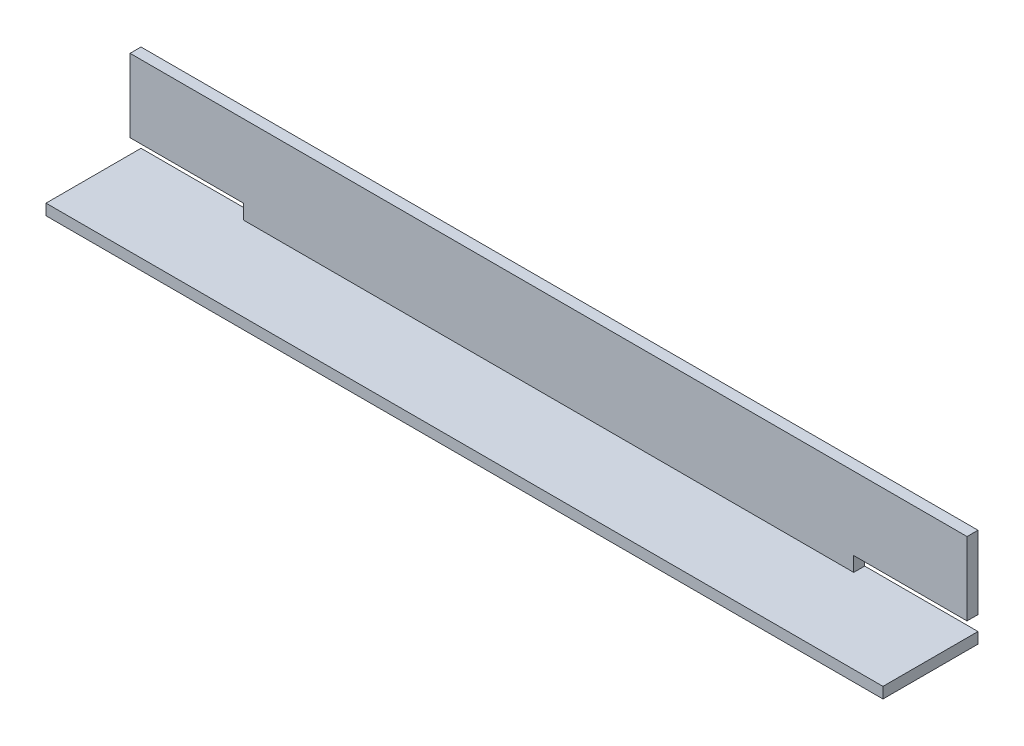
SolidWorks part; units mm, degrees
ref_plane "Front Plane" through (0, 0, 0) normal (0, 0, 1) x (1, 0, 0)
ref_plane "Top Plane" through (0, 0, 0) normal (0, 1, 0) x (1, 0, 0)
ref_plane "Right Plane" through (0, 0, 0) normal (1, 0, 0) x (0, 0, -1)
sketch "Sketch1" plane through (0, 0, 0) normal (0, 1, 0) x (1, 0, 0)
  line L1 (0, 0) -> (-229, 0)
  line L2 (0, 0) -> (0, -26)
  line L3 (0, -26) -> (-229, -26)
  line L4 (-229, 0) -> (-229, -26)
  dimension "D1" = 229
  dimension "D2" = 26
extrude "Boss-Extrude1" add sketch "Sketch1" along normal blind 3
sketch "Sketch2" plane through (0, 3, 0) normal (0, 1, 0) x (1, 0, 0)
  line L0 (0, -26) -> (0, 0) construction
  line L1 (-229, 0) -> (0, 0)
  line L2 (-229, 0) -> (-229, -3)
  line L3 (-229, -3) -> (0, -3)
  line L4 (0, 0) -> (0, -3)
  dimension "D1" = 3
extrude "Boss-Extrude2" add sketch "Sketch2" along normal blind 24
sketch "Sketch3" plane through (0, 0, 3) normal (0, 0, 1) x (1, 0, 0)
  line L1 (-229, 3) -> (-198, 3)
  line L2 (-229, 3) -> (-229, 7)
  line L3 (-229, 7) -> (-198, 7)
  line L4 (-198, 3) -> (-198, 7)
  line L5 (0, 3) -> (-31, 3)
  line L6 (0, 3) -> (0, 7)
  line L7 (0, 7) -> (-31, 7)
  line L8 (-31, 3) -> (-31, 7)
  dimension "D1" = 31
  dimension "D2" = 4
  dimension "D3" = 31
  dimension "D4" = 4
extrude "Cut-Extrude1" cut sketch "Sketch3" against normal blind 24
